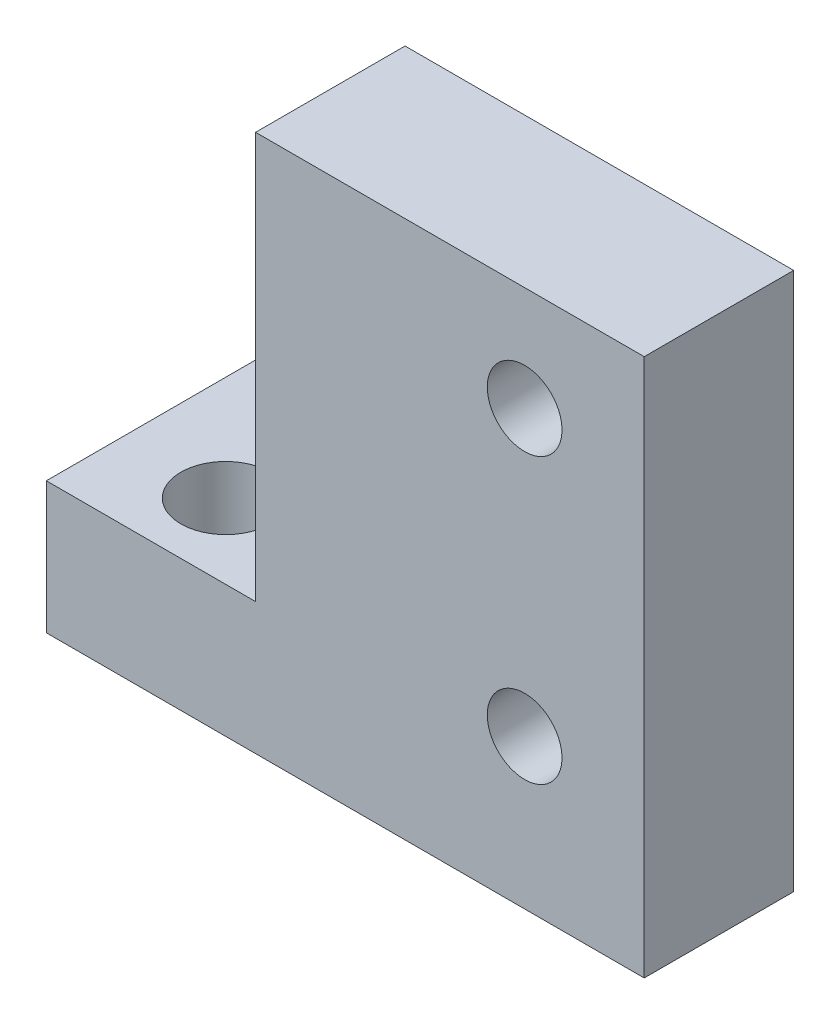
SolidWorks part; units mm, degrees
ref_plane "Front Plane" through (0, 0, 0) normal (0, 0, 1) x (1, 0, 0)
ref_plane "Top Plane" through (0, 0, 0) normal (0, 1, 0) x (1, 0, 0)
ref_plane "Right Plane" through (0, 0, 0) normal (1, 0, 0) x (0, 0, -1)
sketch "Sketch1" plane through (0, 0, 0) normal (0, 1, 0) x (1, 0, 0)
  line L0 (0, 0) -> (0, 6)
  line L1 (0, 0) -> (13, 0)
  line L2 (0, 6) -> (-7, 6)
  line L3 (-7, 6) -> (-7, -5)
  line L4 (-7, -5) -> (13, -5)
  line L5 (13, -5) -> (13, 0)
  dimension "D1" = 6
  dimension "D2" = 13
  dimension "D3" = 7
  dimension "D4" = 5
extrude "Boss-Extrude1" add sketch "Sketch1" along normal blind 18
sketch "Sketch2" plane through (0, 0, 0) normal (1, 0, 0) x (0, 0, -1)
  line L0 (6, 18) -> (6, 0) construction
  line L1 (0, 18) -> (6, 18)
  line L2 (0, 18) -> (0, 4.4044)
  line L3 (0, 4.4044) -> (6, 4.4044)
  line L4 (6, 18) -> (6, 4.4044)
extrude "Cut-Extrude1" cut sketch "Sketch2" against normal blind 10
sketch "Sketch3" plane through (0, 0, 0) normal (0, 0, -1) x (-1, 0, 0)
  line L1 (0, 4.4044) -> (7, 4.4044)
  line L2 (0, 4.4044) -> (0, 18)
  line L3 (0, 18) -> (7, 18)
  line L4 (7, 4.4044) -> (7, 18)
extrude "Cut-Extrude2" cut sketch "Sketch3" against normal blind 10
sketch "Sketch4" plane through (0, 0, 0) normal (0, -1, 0) x (1, 0, 0)
  line L3 (0, 0) -> (0, -6) construction
  circle A0 centre (-1, -2.2) radius 1.5
  dimension "D1" = 1
extrude "Cut-Extrude3" cut sketch "Sketch4" against normal blind 10
hole_wizard "Tap Drill for M3x0.5 Tap1" positions "Sketch6" profile "Sketch5" hole size "M3x0.5" standard "ANSI Metric"
sketch "Sketch6" plane through (0, 0, 0) normal (0, -1, 0) x (-1, 0, 0)
  line L1 (7, 6) -> (7, -5) construction
  point P0 (-3.3, -2.5)
  point P4 (3.5, -2.5)
  dimension "D1" = 6.8
  dimension "D2" = 3.5
sketch "Sketch5" plane through (3.3, 0, 2.5) normal (1, 0, 0) x (0, 0, -1)
  line L0 (0, 0) -> (0, 5)
  line L1 (0, 5) -> (1.5, 5)
  line L2 (1.5, 5) -> (1.5, 0)
  line L5 (1.5, 0) -> (0, 0)
  line L10 (0, 5) -> (-1.5, 5) construction
  line L11 (0, -6.35) -> (0, 107.95) construction
  dimension "Hole Dia." = 3
  dimension "Hole Depth" = 5
  dimension "Drill Angle" = 180
hole_wizard "Ø2.5 (2.5) Diameter Hole1" positions "Sketch8" profile "Sketch7" hole size "Ø2.5" standard "ANSI Metric"
sketch "Sketch8" plane through (0, 0, 0) normal (0, 0, -1) x (-1, 0, 0)
  line L0 (-13, 18) -> (-13, 0) construction
  point P0 (-9, 14.5)
  point P3 (-9, 5)
  dimension "D1" = 4
  dimension "D2" = 4
sketch "Sketch7" plane through (9, 14.5, 0) normal (1, 0, 0) x (0, 1, 0)
  line L0 (0, 0) -> (0, 6.5)
  line L1 (0, 6.5) -> (1.25, 6.5)
  line L2 (1.25, 6.5) -> (1.25, 0)
  line L5 (1.25, 0) -> (0, 0)
  line L10 (0, 6.5) -> (-1.25, 6.5) construction
  line L11 (0, -6.35) -> (0, 107.95) construction
  dimension "Hole Dia." = 2.5
  dimension "Hole Depth" = 6.5
  dimension "Drill Angle" = 180
